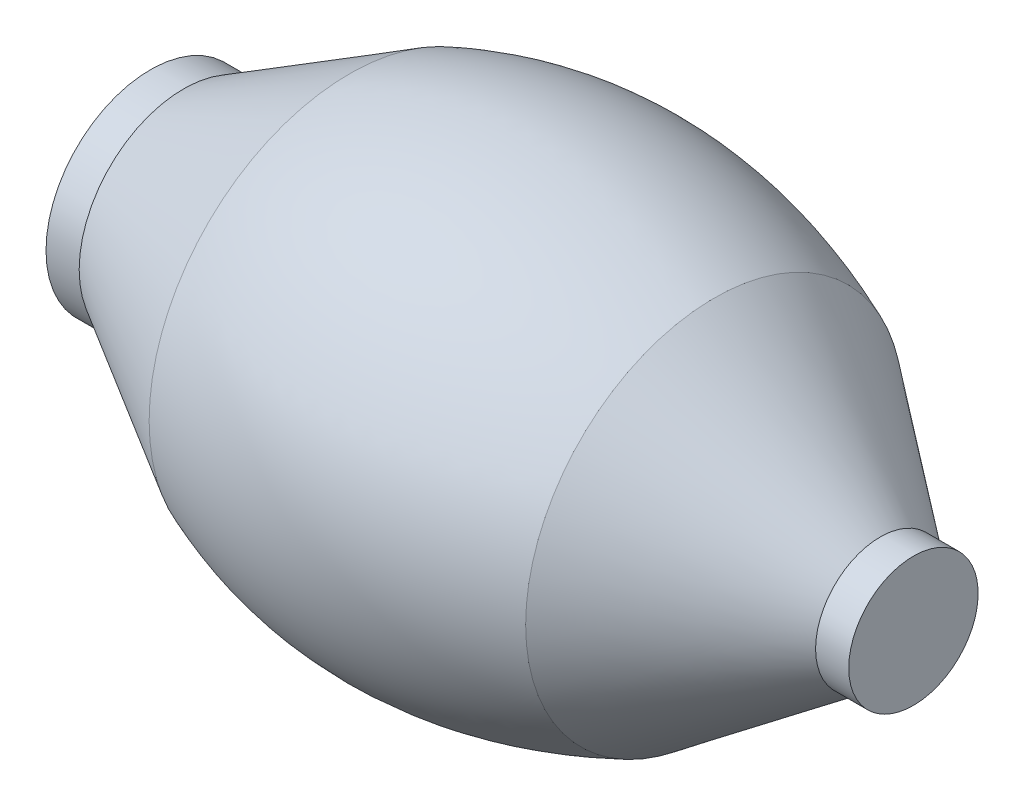
SolidWorks part; units mm, degrees
ref_plane "Front Plane" through (0, 0, 0) normal (0, 0, 1) x (1, 0, 0)
ref_plane "Top Plane" through (0, 0, 0) normal (0, 1, 0) x (1, 0, 0)
ref_plane "Right Plane" through (0, 0, 0) normal (1, 0, 0) x (0, 0, -1)
sketch "Sketch1" plane through (0, 0, 0) normal (0, 1, 0) x (1, 0, 0)
  line L0 (-72.8662, 0) -> (81.9745, 0) construction
  line L1 (-86.5287, 70) -> (81.9745, 70) construction
  line L2 (-50, 60.409) -> (-100, 31.5)
  line L3 (60, 56.9067) -> (110, 19.5)
  line L4 (-100, 31.5) -> (-110, 31.5)
  line L5 (110, 19.5) -> (120, 19.5)
  line L6 (-110, 0) -> (0, 0)
  line L7 (0, 0) -> (120, 0)
  line L10 (120, 19.5) -> (120, 0)
  line L11 (-110, 31.5) -> (-110, 0)
  spline S0 degree 2 poles (-50, 60.409) (2.1115, 81.2062) (60, 56.9067) knots 0 0 0 1 1 1
  dimension "D2" = 70
  dimension "D1" = 110
  dimension "D3" = 110
  dimension "D4" = 19.5
  dimension "D5" = 10
  dimension "D6" = 10
  dimension "D8" = 50
  dimension "D9" = 50
  dimension "D7" = 31.5
revolve "Revolve1" add sketch "Sketch1" angle 360 about L0
ref_plane "Plane2" through (0, 70, 0) normal (0, 1, 0) x (1, 0, 0)
